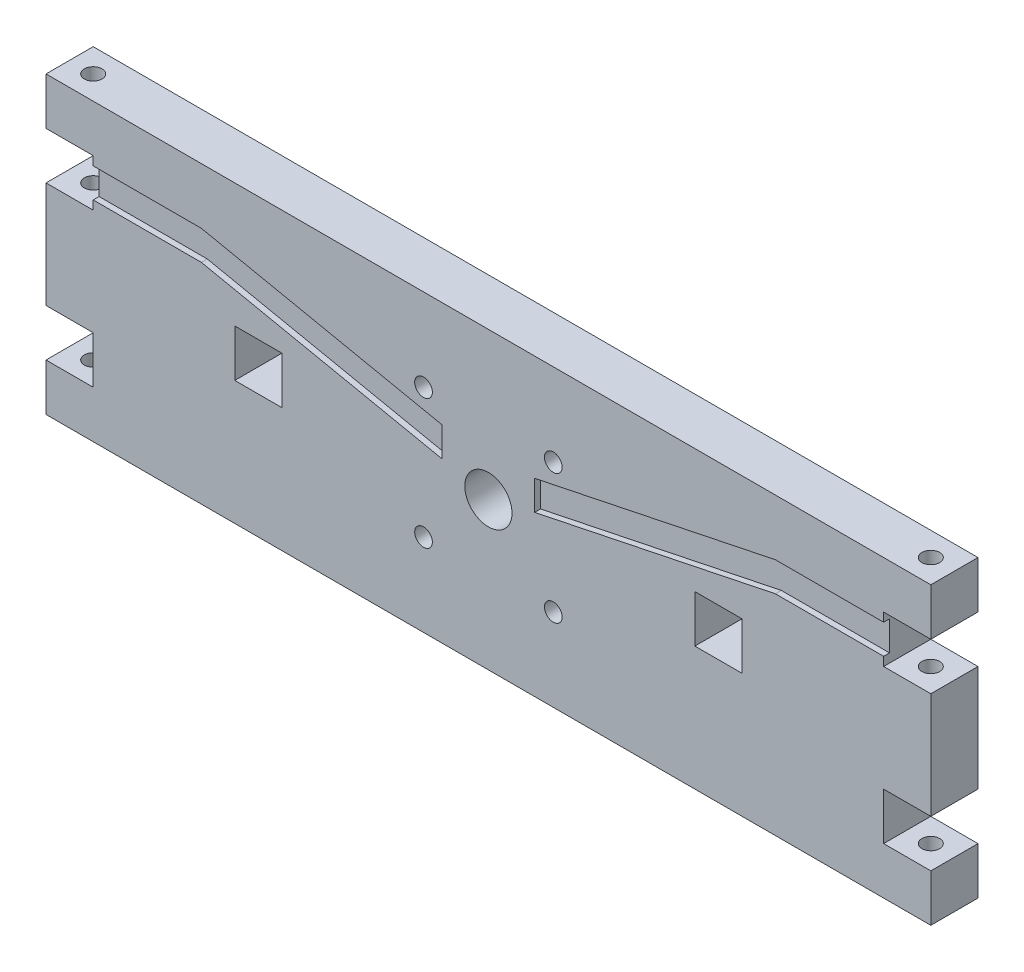
SolidWorks part; units mm, degrees
material "Acrylic (Medium-high impact)"
ref_plane "Front Plane" through (0, 0, 0) normal (0, 0, 1) x (1, 0, 0)
ref_plane "Top Plane" through (0, 0, 0) normal (0, 1, 0) x (1, 0, 0)
ref_plane "Right Plane" through (0, 0, 0) normal (1, 0, 0) x (0, 0, -1)
sketch "Sketch1" plane through (0, 0, 0) normal (0, 0, 1) x (1, 0, 0)
  line L0 (0, 0) -> (0, -25) construction
  line L1 (0, 0) -> (0, 25) construction
  line L2 (0, 0) -> (78.6231, 0) construction
  line L3 (0, 0) -> (-78.6231, 0) construction
  line L5 (75, 25) -> (-75, 25)
  line L6 (75, 25) -> (75, -25)
  line L7 (75, -25) -> (-75, -25)
  line L8 (-75, 25) -> (-75, -25)
  dimension "D1" = 50
  dimension "D2" = 150
extrude "U-Arm Bottom Boss-Extrude1" add sketch "Sketch1" against normal blind 8
sketch "Sketch2" plane through (0, 0, 0) normal (0, 0, 1) x (1, 0, 0)
  line L0 (75, -25) -> (75, 25) construction
  line L1 (75, 9) -> (67, 9)
  line L2 (75, 9) -> (75, 17)
  line L3 (75, 17) -> (67, 17)
  line L4 (67, 9) -> (67, 17)
  line L5 (-75, 25) -> (-75, -25) construction
  line L6 (75, -9) -> (67, -9)
  line L7 (75, -9) -> (75, -17)
  line L8 (75, -17) -> (67, -17)
  line L9 (67, -9) -> (67, -17)
  line L10 (-75, -17) -> (-67, -17)
  line L11 (-75, -17) -> (-75, -9)
  line L12 (-75, -9) -> (-67, -9)
  line L13 (-67, -17) -> (-67, -9)
  line L14 (-67, -17) -> (-67, -25) construction
  line L15 (-75, 17) -> (-67, 17)
  line L16 (-75, 17) -> (-75, 9)
  line L17 (-75, 9) -> (-67, 9)
  line L18 (-67, 17) -> (-67, 9)
  line L19 (-75, -25) -> (75, -25) construction
  line L20 (-67, 17) -> (-67, 25) construction
  line L21 (75, 25) -> (-75, 25) construction
  line L22 (67, 17) -> (67, 25) construction
  line L23 (67, -17) -> (67, -25) construction
  dimension "D1" = 8
extrude "Puzzle Slot Cut-Extrude1" cut sketch "Sketch2" against normal up to surface (8 mm away) up to face at (0, 0, -8)
sketch "Sketch3" plane through (0, 0, 0) normal (0, 0, 1) x (1, 0, 0)
  circle A0 centre (0, 0) radius 4
  dimension "D1" = 8
extrude "Center Shaft Hole Cut-Extrude2" cut sketch "Sketch3" against normal up to surface (8 mm away) up to face at (0, 0, -8)
sketch "Sketch4" plane through (0, -25, 0) normal (0, -1, 0) x (1, 0, 0)
  line L0 (-71, 0) -> (-71, -4) construction
  line L1 (-75, 0) -> (75, 0) construction
  line L2 (-71, -4) -> (-71, -8) construction
  line L3 (-75, -8) -> (75, -8) construction
  line L4 (-71, -4) -> (-75, -4) construction
  line L5 (-75, -8) -> (-75, 0) construction
  line L6 (71, 0) -> (71, -4) construction
  line L7 (71, -4) -> (71, -8) construction
  line L8 (71, -4) -> (75, -4) construction
  line L9 (75, -8) -> (75, 0) construction
  circle A0 centre (-71, -4) radius 1.5
  circle A1 centre (71, -4) radius 1.5
  dimension "D1" = 3
extrude "Puzzle Slot Screw Holes Cut-Extrude3" cut sketch "Sketch4" against normal up to surface (50 mm away) up to face at (0, 25, -4)
sketch "Sketch5" plane through (0, 0, 0) normal (0, 0, 1) x (1, 0, 0)
  line L0 (-35, 4) -> (-35, 0)
  line L2 (-35, 0) -> (-35, -4)
  line L4 (43, 4) -> (43, -4)
  line L5 (35, 4) -> (43, 4)
  line L6 (35, 4) -> (35, 0)
  line L7 (67, -9) -> (67, -17) construction
  line L8 (-67, -17) -> (-67, -9) construction
  line L9 (-35, 4) -> (-43, 4)
  line L11 (43, -4) -> (35, -4)
  line L12 (35, 0) -> (35, -4)
  line L13 (-35, -4) -> (-43, -4)
  line L14 (-43, 4) -> (-43, -4)
  point P5 (-67, -13)
  dimension "D1" = 8
  dimension "D2" = 32
  dimension "D3" = 32
extrude "Side Puzzle Slots Cut-Extrude4" cut sketch "Sketch5" against normal up to surface (8 mm away) up to face at (-4, 0, -8)
sketch "Sketch6" plane through (0, 0, 0) normal (0, 0, 1) x (1, 0, 0)
  line L1 (67, 9) -> (75, 9) construction
  line L2 (67, 15.5) -> (48.6576, 15.5)
  line L3 (67, 15.5) -> (67, 10.5)
  line L4 (67, 10.5) -> (48.6576, 10.5)
  line L6 (-7.8416, 7.0485) -> (-7.8416, 2.0485)
  line L7 (67, 17) -> (67, 9) construction
  line L11 (-67, 9) -> (-67, 17) construction
  line L12 (7.8416, 7.0485) -> (7.8416, 2.0485)
  line L13 (7.8416, 7.0485) -> (48.6576, 15.5)
  line L14 (7.8416, 2.0485) -> (48.6576, 10.5)
  line L15 (-67, 15.5) -> (-48.6576, 15.5)
  line L16 (-67, 15.5) -> (-67, 10.5)
  line L17 (-67, 10.5) -> (-48.6576, 10.5)
  line L18 (-75, 9) -> (-67, 9) construction
  line L21 (-48.6576, 15.5) -> (-7.8416, 7.0485)
  line L23 (-48.6576, 10.5) -> (-7.8416, 2.0485)
  point P5 (71, 9)
  dimension "D1" = 5
  dimension "D2" = 1.5
  dimension "D4" = 5
  dimension "D5" = 5
  dimension "D6" = 5
  dimension "D7" = 1.5
extrude "Cable Cut-Extrude13" cut sketch "Sketch6" against normal blind 1
sketch "Sketch7" plane through (0, 0, 0) normal (0, 0, 1) x (1, 0, 0)
  line L0 (-11, 11) -> (0, 0) construction
  line L1 (11, 11) -> (-11, 11) construction
  line L2 (11, 11) -> (11, -11) construction
  line L3 (11, -11) -> (-11, -11) construction
  line L4 (-11, 11) -> (-11, -11) construction
  line L5 (0, 0) -> (-11, -11) construction
  line L6 (0, 0) -> (11, -11) construction
  line L7 (0, 0) -> (11, 11) construction
  circle A0 centre (11, 11) radius 1.5
  circle A1 centre (-11, 11) radius 1.5
  circle A2 centre (-11, -11) radius 1.5
  circle A3 centre (11, -11) radius 1.5
  dimension "D2" = 3
  dimension "D1" = 22
extrude "Distans Mounting Holes Cut-Extrude1" cut sketch "Sketch7" against normal up to surface (8 mm away) up to face at (-39, 0, -8)
